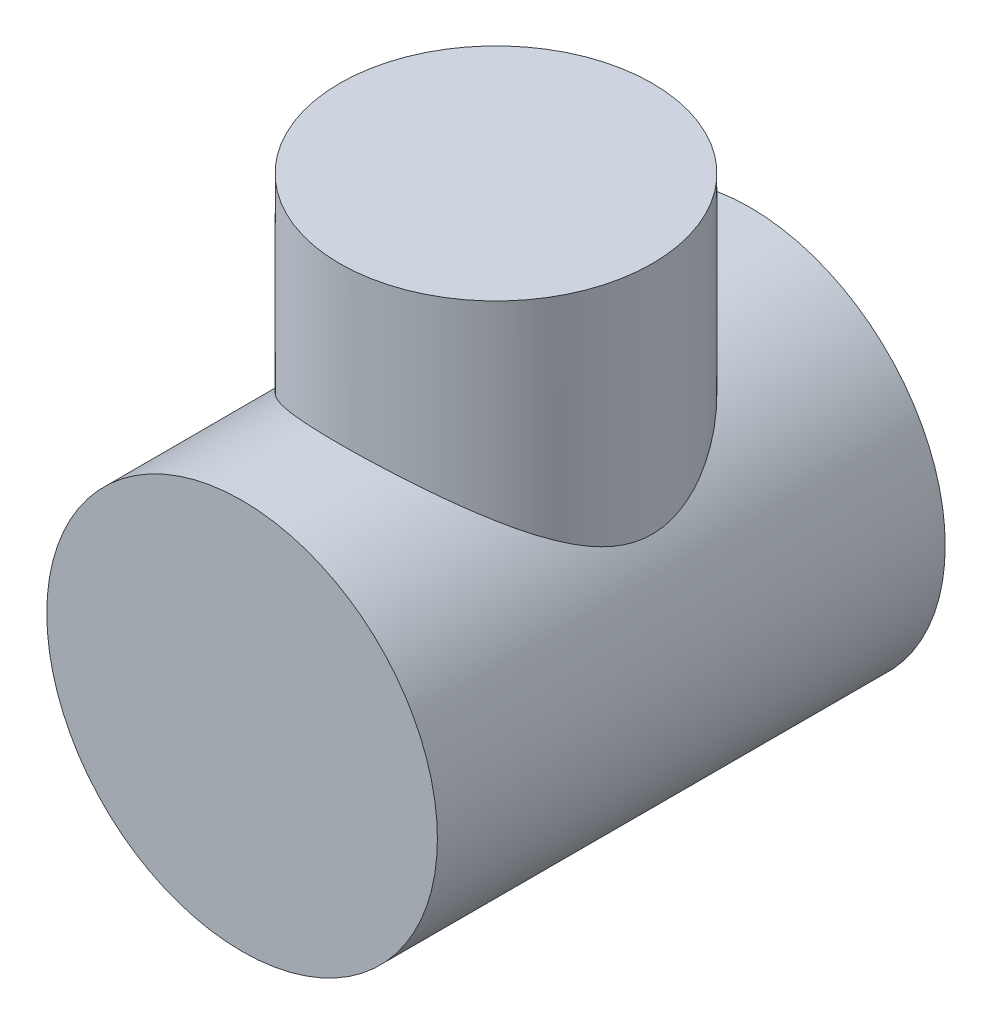
SolidWorks part; units mm, degrees
ref_plane "Front Plane" through (0, 0, 0) normal (0, 0, 1) x (1, 0, 0)
ref_plane "Top Plane" through (0, 0, 0) normal (0, 1, 0) x (1, 0, 0)
ref_plane "Right Plane" through (0, 0, 0) normal (1, 0, 0) x (0, 0, -1)
sketch "Sketch1" plane through (0, 0, 0) normal (0, 1, 0) x (1, 0, 0)
  circle A0 centre (0, 0) radius 2
  dimension "D1" = 4
extrude "Boss-Extrude1" add sketch "Sketch1" along normal blind 4.5
sketch "Sketch3" plane through (0, 0, 0) normal (0, 0, 1) x (1, 0, 0)
  circle A0 centre (0, 0) radius 2.5
  dimension "D1" = 5
extrude "Boss-Extrude2" add sketch "Sketch3" along normal mid plane 6.5
